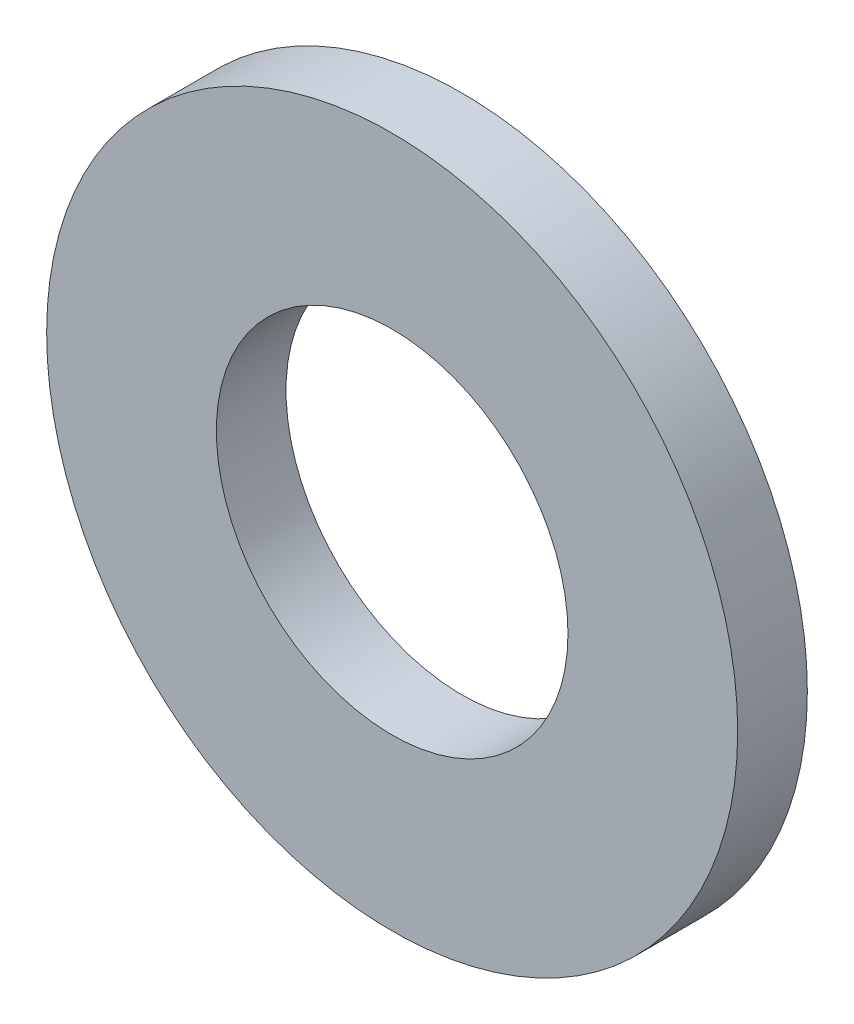
SolidWorks part; units mm, degrees
ref_plane "Front Plane" through (0, 0, 0) normal (0, 0, 1) x (1, 0, 0)
ref_plane "Top Plane" through (0, 0, 0) normal (0, 1, 0) x (1, 0, 0)
ref_plane "Right Plane" through (0, 0, 0) normal (1, 0, 0) x (0, 0, -1)
sketch "Sketch1" plane through (0, 0, 0) normal (0, 0, 1) x (1, 0, 0)
  circle A0 centre (0, 0) radius 4.0386
  circle A1 centre (0, 0) radius 7.9375
extrude "Boss-Extrude1" add sketch "Sketch1" along normal blind 1.6002
